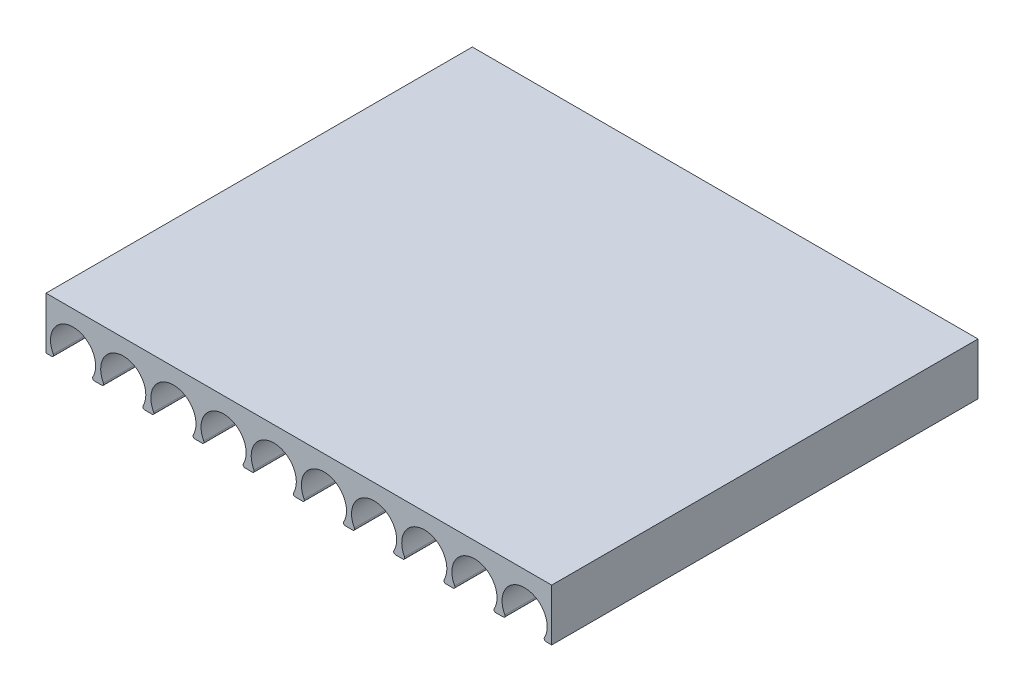
SolidWorks part; units mm, degrees
ref_plane "Front Plane" through (0, 0, 0) normal (0, 0, 1) x (1, 0, 0)
ref_plane "Top Plane" through (0, 0, 0) normal (0, 1, 0) x (1, 0, 0)
ref_plane "Right Plane" through (0, 0, 0) normal (1, 0, 0) x (0, 0, -1)
sketch "Sketch1" plane through (0, 0, 0) normal (0, 0, 1) x (1, 0, 0)
  line L0 (0, 0) -> (1.27, 0)
  line L1 (0.635, 1.905) -> (6.985, 1.905) construction
  line L2 (0, 0) -> (0, 5.715)
  line L3 (0, 5.715) -> (7.62, 5.715)
  line L4 (0, 5.715) -> (3.81, 1.905) construction
  line L5 (6.35, 0) -> (7.62, 0)
  line L6 (7.62, 0) -> (7.62, 5.715)
  line L7 (3.81, 1.905) -> (7.62, 5.715) construction
  arc A0 (1.27, 0) -> (6.35, 0) centre (3.81, 1.905) cw
  dimension "D1" = 6.35
  dimension "D2" = 5.08
  dimension "D3" = 0.635
extrude "Boss-Extrude1" add sketch "Sketch1" along normal mid plane 60
fillet "Fillet1" radius 0.254 2 edges at (1.27, 0, 0) (6.35, 0, 0)
sketch "Sketch2" plane through (0, 0, 30) normal (0, 0, 1) x (1, 0, 0)
  circle A0 centre (3.81, 1.4971) radius 3
  dimension "D1" = 6
pattern_linear "LPattern1" count 10 spacing 7.0612 along (-1, 0, 0) of "Boss-Extrude1", "Fillet1"
sketch "Sketch4" plane through (0, 5.715, 0) normal (0, 1, 0) x (1, 0, 0)
  line L4 (-63.5508, 30) -> (-63.5508, -30)
  line L5 (-63.5508, -30) -> (7.62, -30)
  line L6 (7.62, -30) -> (7.62, 30)
  line L7 (7.62, 30) -> (-63.5508, 30)
  line L8 (-63.5508, 30) -> (-63.5508, -30)
  line L9 (-63.5508, -30) -> (7.62, -30)
  line L10 (7.62, -30) -> (7.62, 30)
  line L11 (7.62, 30) -> (-63.5508, 30)
  dimension "D1" = 0
extrude "Boss-Extrude2" add sketch "Sketch4" along normal blind 1.5875
